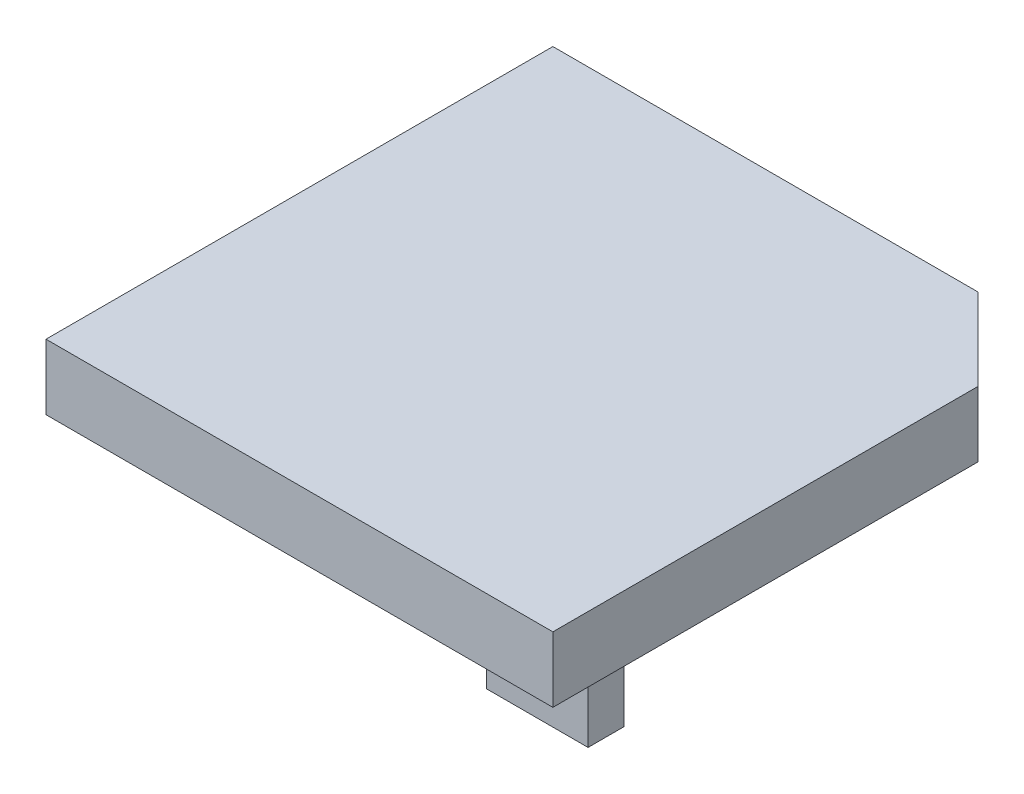
SolidWorks part; units mm, degrees
ref_plane "Front Plane" through (0, 0, 0) normal (0, 0, 1) x (1, 0, 0)
ref_plane "Top Plane" through (0, 0, 0) normal (0, 1, 0) x (1, 0, 0)
ref_plane "Right Plane" through (0, 0, 0) normal (1, 0, 0) x (0, 0, -1)
sketch "Sketch1" plane through (0, 0, 0) normal (0, 1, 0) x (1, 0, 0)
  line L1 (-9.8425, -9.8425) -> (9.8425, -9.8425)
  line L2 (-9.8425, -9.8425) -> (-9.8425, 9.8425)
  line L3 (-9.8425, 9.8425) -> (9.8425, 9.8425)
  line L4 (9.8425, -9.8425) -> (9.8425, 9.8425)
  line L5 (-9.8425, -9.8425) -> (9.8425, 9.8425) construction
  line L6 (-9.8425, 9.8425) -> (9.8425, -9.8425) construction
  point P0 (0, 0)
  dimension "D1" = 19.685
  dimension "D2" = 19.685
extrude "Boss-Extrude1" add sketch "Sketch1" along normal blind 2.54
sketch "Sketch2" plane through (0, 2.54, 0) normal (0, 1, 0) x (1, 0, 0)
  line L0 (-9.8425, 9.8425) -> (-1.4605, 9.8425) construction
  line L1 (9.8425, 9.8425) -> (-9.8425, 9.8425) construction
  line L2 (9.8425, -9.8425) -> (9.8425, 0) construction
  line L3 (9.8425, -9.8425) -> (9.8425, 9.8425) construction
  dimension "D1" = 8.382
sketch "Sketch3" plane through (0, 0, 0) normal (0, -1, 0) x (1, 0, 0)
  line L0 (-9.8425, -9.8425) -> (-1.4605, -9.8425) construction
  line L1 (9.8425, 0) -> (9.8425, 9.8425) construction
  line L2 (-1.4605, -9.8425) -> (-1.4605, 0) construction
  line L3 (-1.4605, 0) -> (9.8425, 0) construction
  line L4 (-4.9848, 9.8425) -> (-4.9847, -9.8425) construction
  line L6 (9.8425, 5.2375) -> (-9.8425, 5.2375) construction
  line L7 (-9.8425, -9.8425) -> (-9.8425, 9.8425) construction
  line L8 (-9.8425, 9.8425) -> (9.8425, 9.8425) construction
  line L14 (-5.6832, -7.0485) -> (-4.2862, -7.0485)
  line L19 (3.3655, 4.539) -> (7.3025, 4.539)
  line L20 (3.3655, 4.539) -> (3.3655, 5.936)
  line L21 (-5.6832, -7.0485) -> (-5.6832, -3.1115)
  line L22 (-5.6832, -3.1115) -> (-4.2862, -3.1115)
  line L23 (-4.2862, -7.0485) -> (-4.2862, -3.1115)
  line L24 (-5.6832, -7.0485) -> (-4.2862, -3.1115) construction
  line L25 (-5.6832, -3.1115) -> (-4.2862, -7.0485) construction
  line L26 (3.3655, 5.936) -> (7.3025, 5.936)
  line L27 (7.3025, 4.539) -> (7.3025, 5.936)
  line L28 (3.3655, 4.539) -> (7.3025, 5.936) construction
  line L29 (3.3655, 5.936) -> (7.3025, 4.539) construction
  point P17 (-4.9847, -5.08)
  point P22 (5.334, 5.2375)
  dimension "D1" = 4.8578
  dimension "D4" = 4.605
  dimension "D5" = 3.937
  dimension "D6" = 1.397
  dimension "D7" = 2.794
  dimension "D8" = 2.54
extrude "Boss-Extrude2" add sketch "Sketch3" along normal blind 4.572
chamfer "Chamfer1" distance 3.175 angle 45 1 edges at (9.8425, 1.27, -9.8425)
